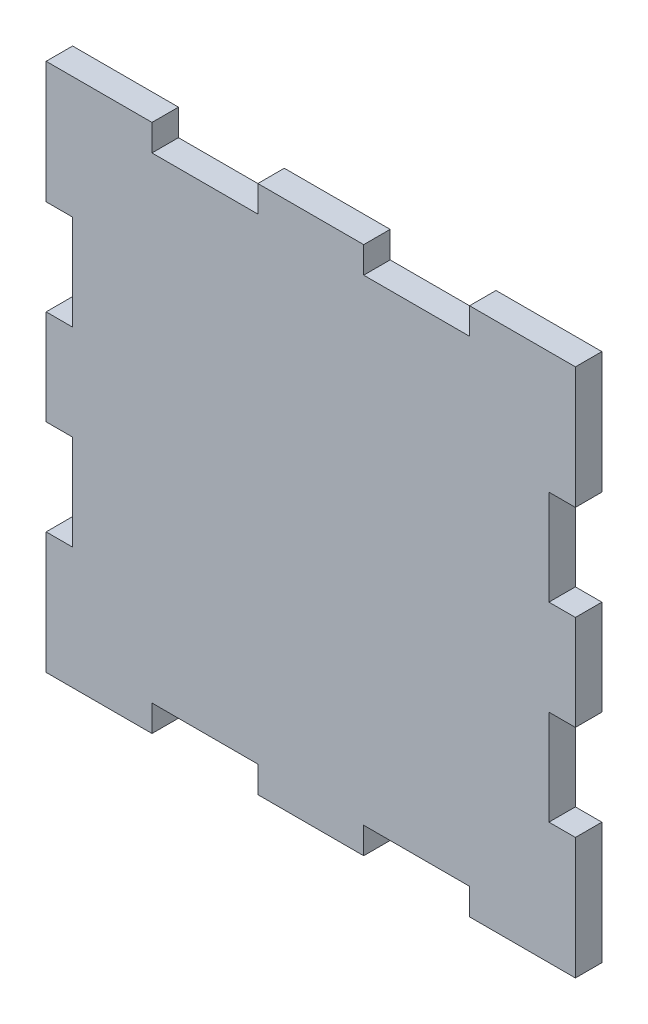
SolidWorks part; units mm, degrees
ref_plane "Front Plane" through (0, 0, 0) normal (0, 0, 1) x (1, 0, 0)
ref_plane "Top Plane" through (0, 0, 0) normal (0, 1, 0) x (1, 0, 0)
ref_plane "Right Plane" through (0, 0, 0) normal (1, 0, 0) x (0, 0, -1)
sketch "Esquisse1" plane through (0, 0, 0) normal (0, 0, 1) x (1, 0, 0)
  line L1 (0, 0) -> (-100, 0)
  line L2 (0, 0) -> (0, -100)
  line L3 (0, -100) -> (-100, -100)
  line L4 (-100, 0) -> (-100, -100)
  line L5 (-50, -100) -> (-50, 0) construction
  line L6 (0, -50) -> (-100, -50) construction
  point P148 (-50, -50)
  dimension "D1" = 100
extrude "Boss.-Extru.1" add sketch "Esquisse1" along normal blind 5
sketch "Esquisse2" plane through (0, 0, 0) normal (0, 0, -1) x (-1, 0, 0)
  line L0 (100, -100) -> (0, -100) construction
  line L1 (80, -95) -> (60, -95)
  line L2 (80, -95) -> (80, -100)
  line L3 (80, -100) -> (60, -100)
  line L4 (60, -95) -> (60, -100)
  line L5 (70, -100) -> (70, -95) construction
  line L6 (80, -97.5) -> (60, -97.5) construction
  line L7 (60, -100) -> (60, -95) construction
  line L8 (20, -100) -> (20, -95) construction
  line L9 (40, -95) -> (20, -95)
  line L10 (40, -95) -> (40, -100)
  line L11 (40, -100) -> (20, -100)
  line L12 (20, -95) -> (20, -100)
  line L13 (30, -100) -> (30, -95) construction
  line L14 (40, -97.5) -> (20, -97.5) construction
  line L15 (100, -50) -> (0, -50) construction
  line L16 (100, 0) -> (100, -100) construction
  line L17 (0, -100) -> (0, 0) construction
  line L18 (40, -2.5) -> (20, -2.5) construction
  line L19 (30, 0) -> (30, -5) construction
  line L20 (80, -2.5) -> (60, -2.5) construction
  line L21 (70, 0) -> (70, -5) construction
  line L22 (20, -5) -> (20, 0)
  line L23 (40, 0) -> (20, 0)
  line L24 (40, -5) -> (40, 0)
  line L25 (40, -5) -> (20, -5)
  line L26 (60, -5) -> (60, 0)
  line L27 (80, 0) -> (60, 0)
  line L28 (80, -5) -> (80, 0)
  line L29 (80, -5) -> (60, -5)
  line L30 (50, -100) -> (50, 0) construction
  line L31 (0, 0) -> (100, 0) construction
  line L32 (95, -59) -> (100, -59) construction
  line L33 (95, -77) -> (100, -77)
  line L34 (95, -77) -> (95, -59)
  line L35 (95, -59) -> (100, -59)
  line L36 (100, -77) -> (100, -59)
  line L37 (97.5, -59) -> (97.5, -77) construction
  line L38 (95, -68) -> (100, -68) construction
  line L39 (95, -23) -> (100, -23) construction
  line L40 (95, -41) -> (100, -41)
  line L41 (95, -41) -> (95, -23)
  line L42 (95, -23) -> (100, -23)
  line L43 (100, -41) -> (100, -23)
  line L44 (97.5, -23) -> (97.5, -41) construction
  line L45 (95, -32) -> (100, -32) construction
  line L46 (5, -32) -> (0, -32) construction
  line L47 (2.5, -23) -> (2.5, -41) construction
  line L48 (0, -41) -> (0, -23)
  line L49 (5, -23) -> (0, -23)
  line L50 (5, -41) -> (5, -23)
  line L51 (5, -41) -> (0, -41)
  line L52 (5, -68) -> (0, -68) construction
  line L53 (2.5, -59) -> (2.5, -77) construction
  line L54 (0, -77) -> (0, -59)
  line L55 (5, -59) -> (0, -59)
  line L56 (5, -77) -> (5, -59)
  line L57 (5, -77) -> (0, -77)
  point P40 (30, -2.5)
  point P41 (70, -2.5)
  point P70 (2.5, -32)
  point P79 (2.5, -68)
  point P112 (70, -97.5)
  point P142 (30, -97.5)
  point P206 (97.5, -32)
  point P266 (97.5, -68)
extrude "Enlèv. mat.-Extru.1" cut sketch "Esquisse2" against normal blind 5
